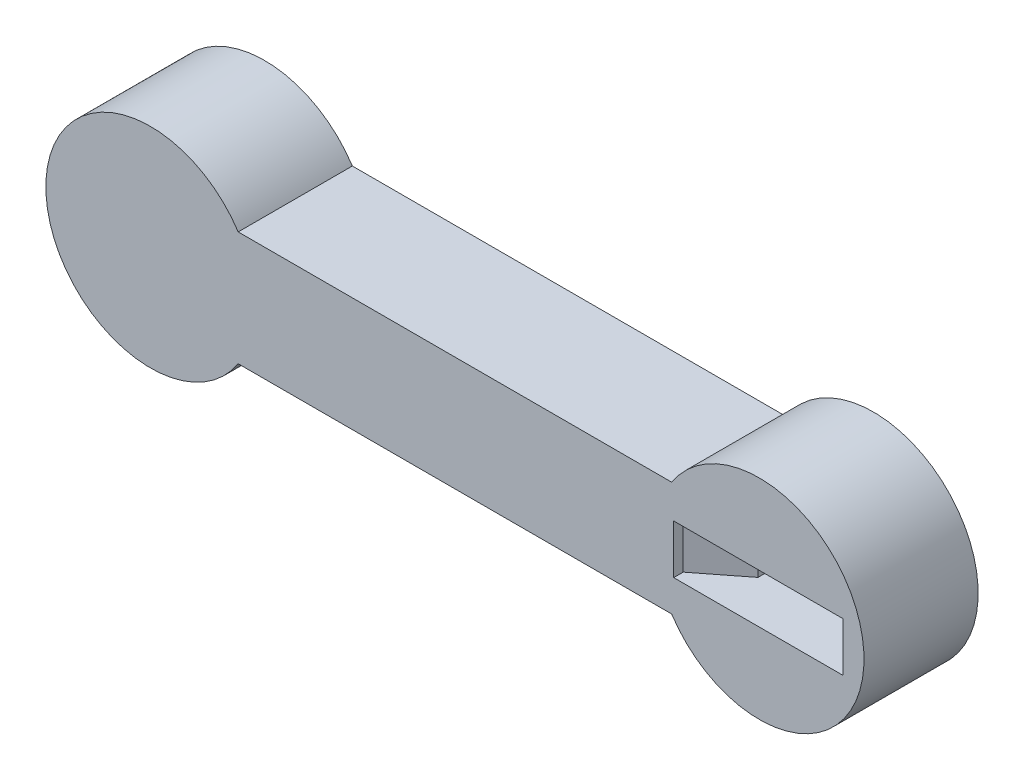
SolidWorks part; units mm, degrees
material "Custom Plastic"
ref_plane "Front Plane" through (0, 0, 0) normal (0, 0, 1) x (1, 0, 0)
ref_plane "Top Plane" through (0, 0, 0) normal (0, 1, 0) x (1, 0, 0)
ref_plane "Right Plane" through (0, 0, 0) normal (1, 0, 0) x (0, 0, -1)
sketch "Sketch1" plane through (0, 0, 0) normal (0, 0, 1) x (1, 0, 0)
  line L1 (0, 15) -> (160, 15)
  line L2 (0, 15) -> (0, -15)
  line L3 (0, -15) -> (160, -15)
  line L4 (160, 15) -> (160, -15)
  circle A0 centre (0, 0) radius 27.5
  circle A1 centre (160, 0) radius 27.5
  circle A2 centre (0, 0) radius 20
  point P9 (0, 0)
  dimension "D1" = 55
  dimension "D4" = 55
  dimension "D5" = 40
  dimension "D2" = 160
  dimension "D3" = 30
extrude "Boss-Extrude1" add sketch "Sketch1" along normal blind 30 contours L3 A1 L1 L4 | A1 L1 A0 L3 | L1 A1 L3 L4 | A2 L3 A0 L1 | A2 L1 A0 L3 | L3 A2 L1 L2 | L1 A2 L3 L2
sketch "Sketch16" plane through (0, 0, 0) normal (0, 0, -1) x (-1, 0, 0)
  line L0 (-136.9511, -15) -> (-148.5193, -6.45) construction
  line L1 (-148.5193, -6.45) -> (-181.9193, -6.45)
  line L2 (-148.5193, -6.45) -> (-148.5193, 6.45)
  line L3 (-148.5193, 6.45) -> (-181.9193, 6.45)
  line L4 (-181.9193, -6.45) -> (-181.9193, 6.45)
  line L5 (-23.0489, -15) -> (-136.9511, -15) construction
  line L7 (-148.5193, 6.45) -> (-136.9511, 15) construction
  arc A1 (-136.9511, 15) -> (-136.9511, -15) centre (-160, 0) ccw construction
  dimension "D1" = 11.5682
  dimension "D2" = 33.4
  dimension "D3" = 12.9
extrude "Cut-Extrude10" cut sketch "Sketch16" against normal blind 4.5
sketch "Sketch17" plane through (0, 0, 0) normal (0, 0, -1) x (-1, 0, 0)
  line L1 (-176.95, 6.45) -> (-153.4979, 6.45)
  line L2 (-176.95, 6.45) -> (-176.95, -6.45)
  line L3 (-176.95, -6.45) -> (-153.4979, -6.45)
  line L4 (-148.5193, -6.45) -> (-148.5193, 6.45)
  line L5 (-148.5193, 6.45) -> (-181.9193, 6.45)
  line L6 (-181.9193, 6.45) -> (-181.9193, -6.45)
  line L7 (-181.9193, -6.45) -> (-148.5193, -6.45)
  line L8 (-148.5193, -6.45) -> (-148.5193, 6.45)
  line L9 (-148.5193, 6.45) -> (-181.9193, 6.45)
  line L10 (-181.9193, 6.45) -> (-181.9193, -6.45)
  line L11 (-181.9193, -6.45) -> (-148.5193, -6.45)
  line L12 (-153.4979, 6.45) -> (-153.4979, -6.45)
  line M9 (-181.9193, 6.45) -> (-148.5193, 6.45)
  line M11 (-148.5193, -6.45) -> (-181.9193, -6.45)
  dimension "D1" = 0
extrude "Cut-Extrude11" cut sketch "Sketch17" against normal through all contours L12 L2 M9 M11
ref_plane "Plane1" through (0, 0, 0) normal (0, -1, 0) x (-1, 0, 0)
sketch "Sketch18" plane through (0, 0, 0) normal (0, -1, 0) x (-1, 0, 0)
  line L0 (-153.4979, -30) -> (-153.4979, -15)
  line L6 (-137.4979, -30) -> (-137.4979, -27.5)
  line L8 (-181.9193, -4.5) -> (-176.95, -4.5)
  line L9 (-176.95, -4.5) -> (-176.95, -30)
  line L10 (-176.95, -30) -> (-153.4979, -30)
  line L11 (-153.4979, -30) -> (-153.4979, -4.5)
  line L12 (-153.4979, -4.5) -> (-148.5193, -4.5)
  line L13 (-148.5193, -4.5) -> (-148.5193, 0)
  line L14 (-148.5193, 0) -> (-181.9193, 0)
  line L15 (-181.9193, 0) -> (-181.9193, -4.5)
  line L16 (-181.9193, -4.5) -> (-176.95, -4.5)
  line L17 (-176.95, -4.5) -> (-176.95, -30)
  line L18 (-176.95, -30) -> (-153.4979, -30)
  line L19 (-153.4979, -30) -> (-153.4979, -4.5)
  line L20 (-153.4979, -4.5) -> (-148.5193, -4.5)
  line L21 (-148.5193, -4.5) -> (-148.5193, 0)
  line L22 (-148.5193, 0) -> (-181.9193, 0)
  line L23 (-181.9193, 0) -> (-181.9193, -4.5)
  line L26 (-137.4979, -27.5) -> (-153.4979, -15)
  line L28 (-23.0489, -30) -> (-136.9511, -30) construction
  line L30 (-153.4979, -30) -> (-137.4979, -30)
  line L31 (-153.4979, -15) -> (-153.4979, -30)
  dimension "D2" = 15
  dimension "D3" = 16
  dimension "D4" = 2.5
  dimension "D1" = 0
extrude "Cut-Extrude13" cut sketch "Sketch18" against normal mid plane 12.9
sketch "Sketch19" plane through (0, 0, 0) normal (0, 0, -1) x (-1, 0, 0)
  circle A0 centre (0, 0) radius 20
extrude "Cut-Extrude14" cut sketch "Sketch19" against normal blind 8.8 contours A0
ref_plane "Plane2" through (0, 0, 6.5) normal (0, 0, -1) x (-1, 0, 0)
sketch "Sketch21" plane through (0, 0, 6.5) normal (0, 0, -1) x (-1, 0, 0)
  line L0 (-181.9193, 6.45) -> (-181.9193, -6.45) construction
  line L1 (-181.9193, 6.45) -> (-148.5193, 6.45)
  line L2 (-181.9193, 6.45) -> (-181.9193, -6.45)
  line L3 (-181.9193, -6.45) -> (-148.5193, -6.45)
  line L4 (-148.5193, 6.45) -> (-148.5193, -6.45)
  line L5 (-181.9193, -6.45) -> (-148.5193, -6.45) construction
  dimension "D1" = 33.4
  dimension "D2" = 12.9
extrude "Cut-Extrude15" cut sketch "Sketch21" against normal through all
sketch "Sketch23" plane through (0, 0, 0) normal (0, 0, -1) x (-1, 0, 0)
  circle A0 centre (-151.7193, 0) radius 1.1
  circle A1 centre (-178.7193, 0) radius 1.1
extrude "Cut-Extrude16" cut sketch "Sketch23" against normal through all contours A0 | A1
